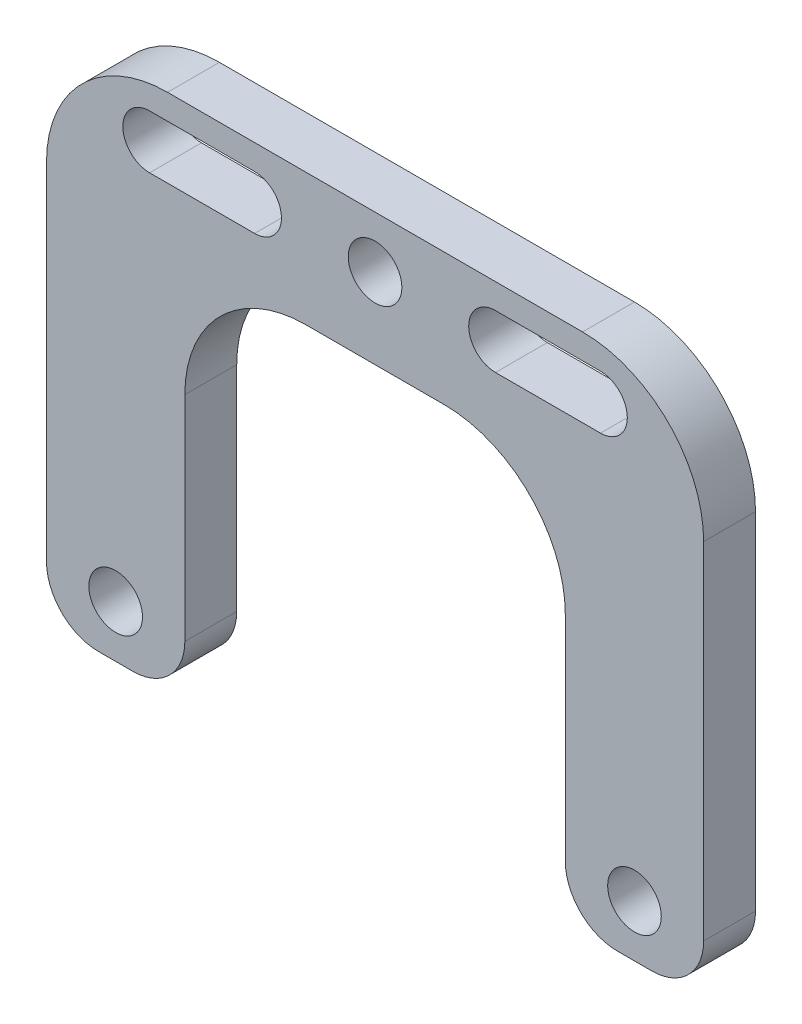
SolidWorks part; units mm, degrees
ref_plane "前视基准面" through (0, 0, 0) normal (0, 0, 1) x (1, 0, 0)
ref_plane "上视基准面" through (0, 0, 0) normal (0, 1, 0) x (1, 0, 0)
ref_plane "右视基准面" through (0, 0, 0) normal (1, 0, 0) x (0, 0, -1)
sketch "草图1" plane through (0, 0, 0) normal (0, 0, 1) x (1, 0, 0)
  line L1 (19, -15) -> (-19, -15)
  line L2 (19, -15) -> (19, 15)
  line L3 (19, 15) -> (-19, 15)
  line L4 (-19, -15) -> (-19, 15)
  line L5 (19, -15) -> (-19, 15) construction
  line L6 (19, 15) -> (-19, -15) construction
  point P0 (0, 0)
  dimension "D1" = 38
  dimension "D2" = 30
extrude "凸台-拉伸1" add sketch "草图1" along normal blind 3
sketch "草图2" plane through (0, 0, 3) normal (0, 0, 1) x (1, 0, 0)
  line L0 (19, 15) -> (-19, 15) construction
  line L1 (6.9637, 12) -> (13.0363, 12) construction
  line L2 (0, 12) -> (0, 15) construction
  line L3 (6.9637, 13.55) -> (13.0363, 13.55)
  line L4 (6.9637, 10.45) -> (13.0363, 10.45)
  line L5 (-6.9637, 12) -> (-13.0363, 12) construction
  line L6 (-6.9637, 13.55) -> (-13.0363, 13.55)
  line L7 (-6.9637, 10.45) -> (-13.0363, 10.45)
  line L9 (-19, -15) -> (19, -15) construction
  circle A0 centre (0, 12) radius 1.55
  arc A1 (6.9637, 13.55) -> (6.9637, 10.45) centre (6.9637, 12) ccw
  arc A2 (13.0363, 10.45) -> (13.0363, 13.55) centre (13.0363, 12) ccw
  arc A3 (-6.9637, 13.55) -> (-6.9637, 10.45) centre (-6.9637, 12) cw
  arc A4 (-13.0363, 10.45) -> (-13.0363, 13.55) centre (-13.0363, 12) cw
  circle A5 centre (-15, -12) radius 1.55
  circle A6 centre (15, -12) radius 1.55
  point P8 (10, 12)
  point P16 (-10, 12)
  point P24 (-15.0874, -15)
  dimension "D1" = 3.1
  dimension "D4" = 3.1
  dimension "D6" = 3
  dimension "D2" = 3
  dimension "D3" = 10
  dimension "D5" = 15
extrude "切除-拉伸1" cut sketch "草图2" against normal blind 10
sketch "草图3" plane through (0, 0, 3) normal (0, 0, 1) x (1, 0, 0)
  line L0 (-11, -15) -> (-11, 7.3589)
  line L1 (-19, -15) -> (19, -15) construction
  line L2 (-11, 7.3589) -> (11, 7.3589)
  line L3 (0, 7.3589) -> (0, 0) construction
  line L4 (11, -15) -> (11, 7.3589)
  line L5 (11, -15) -> (-11, -15)
  point P7 (0, 7.3589)
  dimension "D1" = 11
extrude "切除-拉伸2" cut sketch "草图3" against normal blind 10 contours L5 L0 L2 L4
fillet "圆角1" radius 7 2 edges at (19, 15, 1.5) (-19, 15, 1.5)
fillet "圆角2" radius 7 2 edges at (11, 7.3589, 1.5) (-11, 7.3589, 1.5)
fillet "圆角3" radius 3 4 edges at (19, -15, 1.5) (11, -15, 1.5) (-11, -15, 1.5) (-19, -15, 1.5)
equation "\"3。1\"=0.1"
